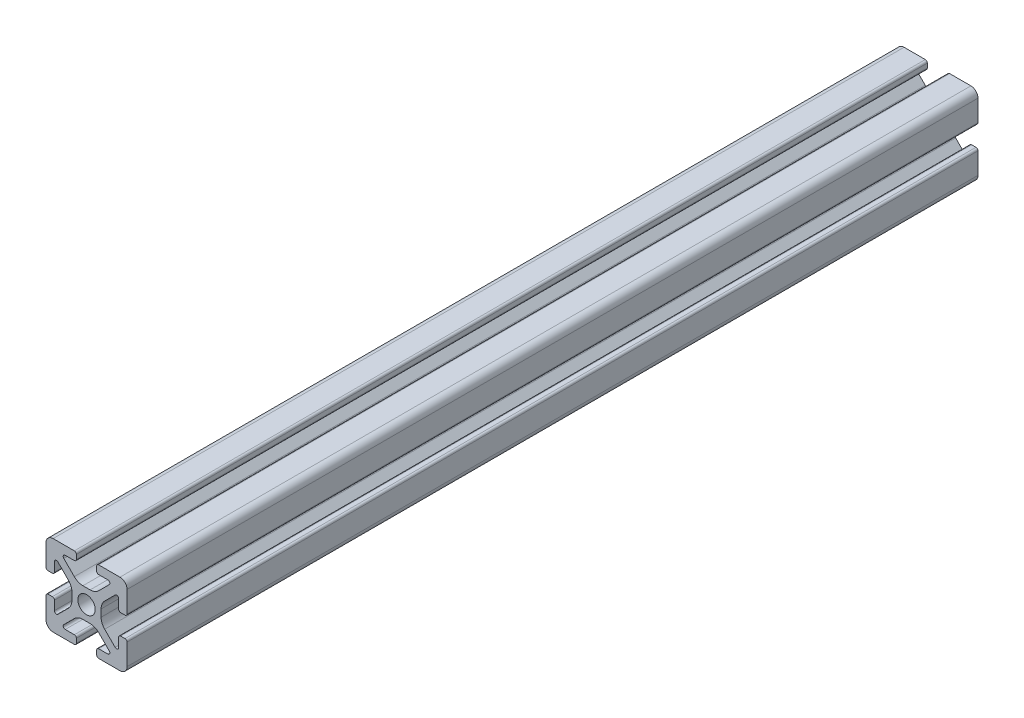
SolidWorks part; units mm, degrees
ref_plane "Front Plane" through (0, 0, 0) normal (0, 0, 1) x (1, 0, 0)
ref_plane "Top Plane" through (0, 0, 0) normal (0, 1, 0) x (1, 0, 0)
ref_plane "Right Plane" through (0, 0, 0) normal (1, 0, 0) x (0, 0, -1)
sketch "Sketch2" plane through (0, 0, 0) normal (0, 0, 1) x (1, 0, 0)
  line L0 (0, 10) -> (0, -10) construction
  line L1 (-10, 0) -> (10, 0) construction
  line L2 (2.5, -10) -> (10, -10)
  line L3 (10, -10) -> (10, -2.5)
  line L4 (2.5, -10) -> (2.5, -7.9246)
  line L5 (2.5, -7.9246) -> (6.4571, -7.9246)
  line L6 (6.4571, -7.9246) -> (2.1325, -3.6)
  line L7 (0, 0) -> (10, -10) construction
  line L8 (10, -2.5) -> (7.9246, -2.5)
  line L9 (7.9246, -2.5) -> (7.9246, -6.4571)
  line L10 (7.9246, -6.4571) -> (3.6, -2.1325)
  line L11 (5.7623, -4.2948) -> (4.2948, -5.7623) construction
  circle A0 centre (0, 0) radius 2.15
  arc A1 (5.25, -7.9246) -> (5.6036, -7.0711) centre (5.25, -7.4246) ccw construction
  point P8 (0, -3.6)
  point P16 (5.0286, -5.0286)
  dimension "Center Hole Diameter" = 4.3
  dimension "D3" = 0.5
  dimension "Rail Height" = 20
  dimension "Rail Width" = 20
  dimension "T-Slot Width" = 5
  dimension "Slot Depth" = 6.4
  dimension "Slot Inner Width" = 11.5
sketch "Sketch3" plane through (0, 0, 0) normal (1, 0, 0) x (0, 0, -1)
  line L0 (-304.8, -10) -> (304.8, -10) construction
  line L1 (-279.4, 0) -> (279.4, 0) construction
  line L2 (0, 10) -> (0, -10) construction
  line L3 (0, 10) -> (0, -10) construction
  point P6 (-279.4, 0)
  point P8 (279.4, 0)
  dimension "Length" = 609.6
  dimension "D1" = 25.4
sketch "Sketch4" plane through (0, 0, 0) normal (0, 0, 1) x (1, 0, 0)
  line L0 (3, -10) -> (8.25, -10)
  line L1 (2.5, -10) -> (10, -10) construction
  line L2 (2.5, -10) -> (2.5, -7.9246) construction
  line L3 (2.5, -7.9246) -> (6.4571, -7.9246) construction
  line L4 (2.5, -8.4246) -> (2.5, -9.5)
  line L5 (3, -7.9246) -> (5.25, -7.9246)
  line L6 (0, -3.6) -> (0.8898, -3.6)
  line L7 (6.4571, -7.9246) -> (2.1325, -3.6) construction
  line L8 (3.0112, -4.4787) -> (5.6036, -7.0711)
  line L9 (10, -10) -> (10, -2.5) construction
  line L10 (7.9246, -6.4571) -> (3.6, -2.1325) construction
  line L11 (7.9246, -2.5) -> (7.9246, -6.4571) construction
  line L12 (7.9246, -5.25) -> (7.9246, -3)
  line L13 (10, -2.5) -> (7.9246, -2.5) construction
  line L14 (8.4246, -2.5) -> (9.5, -2.5)
  line L15 (10, -3) -> (10, -8.25)
  line L16 (7.0711, -5.6036) -> (4.4787, -3.0112)
  line L17 (3.6, 0) -> (3.6, -0.8898)
  line L18 (-10, 0) -> (10, 0) construction
  line L19 (0, -3.6) -> (0, -2.15)
  line L20 (0, 10) -> (0, -10) construction
  line L21 (3.6, 0) -> (2.15, 0)
  arc A0 (2.5, -9.5) -> (3, -10) centre (3, -9.5) ccw
  arc A1 (5.25, -7.9246) -> (5.6036, -7.0711) centre (5.25, -7.4246) ccw construction
  arc A2 (2.5, -8.4246) -> (3, -7.9246) centre (3, -8.4246) cw
  arc A3 (5.25, -7.9246) -> (5.6036, -7.0711) centre (5.25, -7.4246) ccw
  arc A4 (0.8898, -3.6) -> (3.0112, -4.4787) centre (0.8898, -6.6) cw
  arc A5 (8.25, -10) -> (10, -8.25) centre (8.25, -8.25) ccw
  arc A6 (7.0711, -5.6036) -> (7.9246, -5.25) centre (7.4246, -5.25) ccw
  arc A7 (7.9246, -3) -> (8.4246, -2.5) centre (8.4246, -3) cw
  arc A8 (9.5, -2.5) -> (10, -3) centre (9.5, -3) cw
  arc A9 (4.4787, -3.0112) -> (3.6, -0.8898) centre (6.6, -0.8898) cw
  circle A10 centre (0, 0) radius 2.15 construction
  arc A11 (0, -2.15) -> (2.15, 0) centre (0, 0) ccw
  dimension "D1" = 1.75
  dimension "D2" = 3
extrude "Boss-Extrude1" add sketch "Sketch4" along normal mid plane 609.6
mirror "Mirror1" about plane through (0, 0, 0) normal (1, 0, 0) of bodies 134
mirror "Mirror2" about plane through (0, 0, 0) normal (0, 1, 0) of bodies 135
sketch "Sketch5" plane through (0, 0, -304.8) normal (0, 0, -1) x (-1, 0, 0)
  line L1 (-13.8311, 12.3183) -> (13.1641, 12.3183)
  line L2 (-13.8311, 12.3183) -> (-13.8311, -12.3688)
  line L3 (-13.8311, -12.3688) -> (13.1641, -12.3688)
  line L4 (13.1641, 12.3183) -> (13.1641, -12.3688)
extrude "Cut-Extrude1" cut sketch "Sketch5" against normal blind 399.6
equation "\"D3@Sketch2\"=\"T-Slot Width@Sketch2\"*0.1"
equation "\"D1@Sketch4\"=\"D3@Sketch2\"*3.5"
equation "\"D2@Sketch4\"=\"D3@Sketch2\"*6"
equation "\"D1@Boss-Extrude1\"=\"Length@Sketch3\""
